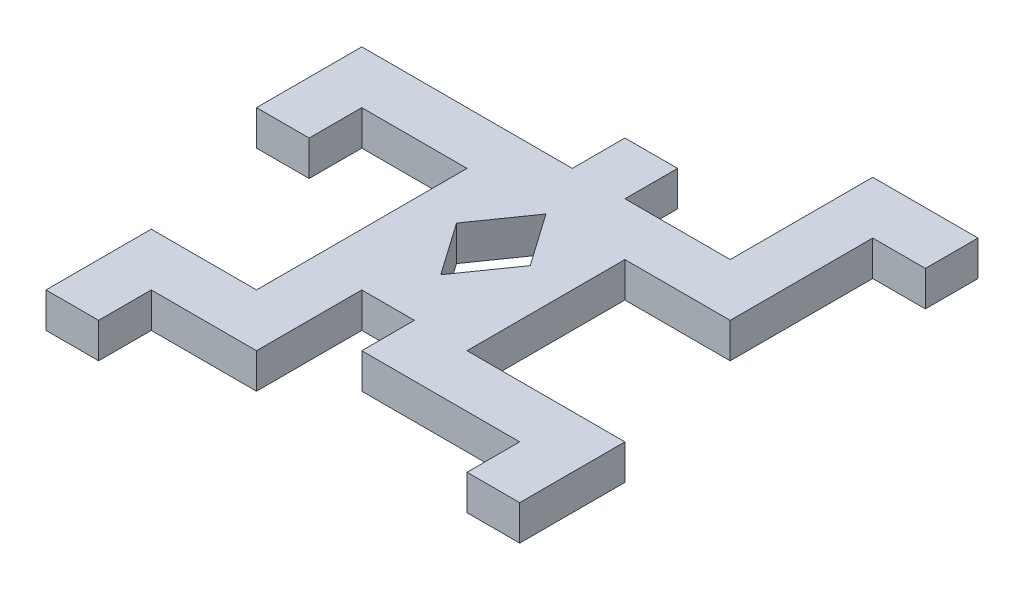
SolidWorks part; units mm, degrees
ref_plane "Front Plane" through (0, 0, 0) normal (0, 0, 1) x (1, 0, 0)
ref_plane "Top Plane" through (0, 0, 0) normal (0, 1, 0) x (1, 0, 0)
ref_plane "Right Plane" through (0, 0, 0) normal (1, 0, 0) x (0, 0, -1)
sketch "Sketch1" plane through (0, 0, 0) normal (0, 1, 0) x (1, 0, 0)
  line L1 (-11.25, 15) -> (11.25, 15)
  line L2 (-11.25, 15) -> (-11.25, -15)
  line L3 (-11.25, -15) -> (11.25, -15)
  line L4 (11.25, 15) -> (11.25, -15)
  line L5 (-11.25, 15) -> (11.25, -15) construction
  line L6 (-11.25, -15) -> (11.25, 15) construction
  line L7 (-3.75, 15) -> (3.75, 15)
  line L8 (-3.75, 15) -> (-3.75, 22.5)
  line L9 (-3.75, 22.5) -> (3.75, 22.5)
  line L10 (3.75, 15) -> (3.75, 22.5)
  line L12 (11.25, 15) -> (11.25, 7.5)
  line L19 (11.25, 15) -> (18.75, 15)
  line L20 (18.75, 15) -> (18.75, 35.3132)
  line L21 (18.75, 35.3132) -> (33.75, 35.3132)
  line L22 (33.75, 35.3132) -> (33.75, 27.8132)
  line L23 (33.75, 27.8132) -> (26.25, 27.8132)
  line L24 (26.25, 27.8132) -> (26.25, 7.5)
  line L25 (26.25, 7.5) -> (11.25, 7.5)
  line L26 (-11.25, 15) -> (-33.75, 15)
  line L27 (-33.75, 15) -> (-33.75, 0)
  line L28 (-33.75, 0) -> (-26.25, 0)
  line L29 (-26.25, 0) -> (-26.25, 7.5)
  line L30 (-26.25, 7.5) -> (-11.25, 7.5)
  line L31 (3.75, -15) -> (3.75, -22.5)
  line L32 (3.75, -22.5) -> (26.25, -22.5)
  line L33 (26.25, -22.5) -> (26.25, -30)
  line L34 (26.25, -30) -> (33.75, -30)
  line L35 (33.75, -30) -> (33.75, -15)
  line L36 (33.75, -15) -> (11.25, -15)
  line L37 (-11.25, -15) -> (-11.25, -22.5)
  line L38 (-11.25, -22.5) -> (-26.25, -22.5)
  line L39 (-26.25, -22.5) -> (-26.25, -37.5)
  line L40 (-26.25, -37.5) -> (-18.75, -37.5)
  line L41 (-18.75, -37.5) -> (-18.75, -30)
  line L42 (-18.75, -30) -> (-3.75, -30)
  line L43 (-3.75, -30) -> (-3.75, -15)
  point P0 (0, 0)
  dimension "D1" = 30
  dimension "D2" = 22.5
  dimension "D3" = 7.5
  dimension "D4" = 7.5
  dimension "D5" = 7.5
  dimension "D6" = 15
  dimension "D7" = 7.5
  dimension "D8" = 7.5
  dimension "D9" = 7.5
  dimension "D10" = 7.5
  dimension "D11" = 22.5
  dimension "D12" = 15
  dimension "D13" = 7.5
  dimension "D14" = 7.5
  dimension "D15" = 22.5
  dimension "D16" = 7.5
  dimension "D17" = 7.5
  dimension "D18" = 15
  dimension "D19" = 7.5
  dimension "D20" = 7.5
  dimension "D21" = 15
  dimension "D22" = 7.5
  dimension "D23" = 7.5
  dimension "D24" = 7.5
  dimension "D25" = 15
extrude "Boss-Extrude1" add sketch "Sketch1" along normal blind 5 contours L29 L30 L2 L26 L27 L28 | L4 L1 L2 L3 | L1 L10 L9 L8 | L25 L24 L23 L22 L21 L20 L19 L4 | L35 L36 L3 L31 L32 L33 L34 | L42 L43 L3 L37 L38 L39 L40 L41
sketch "Sketch2" plane through (0, 5, 0) normal (0, 1, 0) x (1, 0, 0)
  line L0 (-11.25, 7.5) -> (11.25, 7.5) construction
  line L1 (11.25, -7.5) -> (-11.25, -7.5) construction
  line L2 (11.25, 7.5) -> (11.25, -15) construction
  line L3 (-11.25, 7.5) -> (-11.25, -22.5) construction
  line L4 (0, 7.5) -> (-5.25, 0)
  line L5 (-5.25, 0) -> (0, -7.5)
  line L6 (0, -7.5) -> (5.25, 0)
  line L7 (5.25, 0) -> (0, 7.5)
  dimension "D1" = 15
  dimension "D2" = 5.25
extrude "Cut-Extrude1" cut sketch "Sketch2" against normal through all
equation "\"Square Width\" = 7.5mm"
equation "\"Square Height\"= 7.5mm"
equation "\"Tolerance\"= 1mm"
equation "\"Block Height\" = 5mm"
equation "\"Base Height\"= 10mm"
equation "\"D1@Sketch1\"=\"Square Height\"*4"
equation "\"D2@Sketch1\"=\"Square Width\"*3"
equation "\"D3@Sketch1\"=\"Square Width\""
equation "\"D4@Sketch1\"=\"Square Height\""
equation "\"D5@Sketch1\"=\"Square Width\""
equation "\"D6@Sketch1\"=\"Square Width\"*2"
equation "\"D7@Sketch1\"=\"Square Height\""
equation "\"D8@Sketch1\"=\"Square Width\""
equation "\"D9@Sketch1\"=\"Square Height\""
equation "\"D10@Sketch1\"=\"Square Width\""
equation "\"D11@Sketch1\"=\"Square Width\"*3"
equation "\"D12@Sketch1\"=\"Square Height\"*2"
equation "\"D13@Sketch1\"=\"Square Height\""
equation "\"D14@Sketch1\"=\"Square Width\""
equation "\"D15@Sketch1\"=\"Square Width\"*3"
equation "\"D16@Sketch1\"=\"Square Height\""
equation "\"D17@Sketch1\"=\"Square Width\""
equation "\"D18@Sketch1\"=\"Square Height\"*2"
equation "\"D19@Sketch1\"=\"Square Width\""
equation "\"D20@Sketch1\"=\"Square Height\""
equation "\"D21@Sketch1\"=\"Square Width\"*2"
equation "\"D22@Sketch1\"=\"Square Width\""
equation "\"D23@Sketch1\"=\"Square Height\""
equation "\"D24@Sketch1\"=\"Square Width\""
equation "\"D25@Sketch1\"=\"Square Height\"*2"
equation "\"D1@Boss-Extrude1\"=\"Block Height\""
equation "\"D1@Sketch2\"=\"Square Height\"*2"
